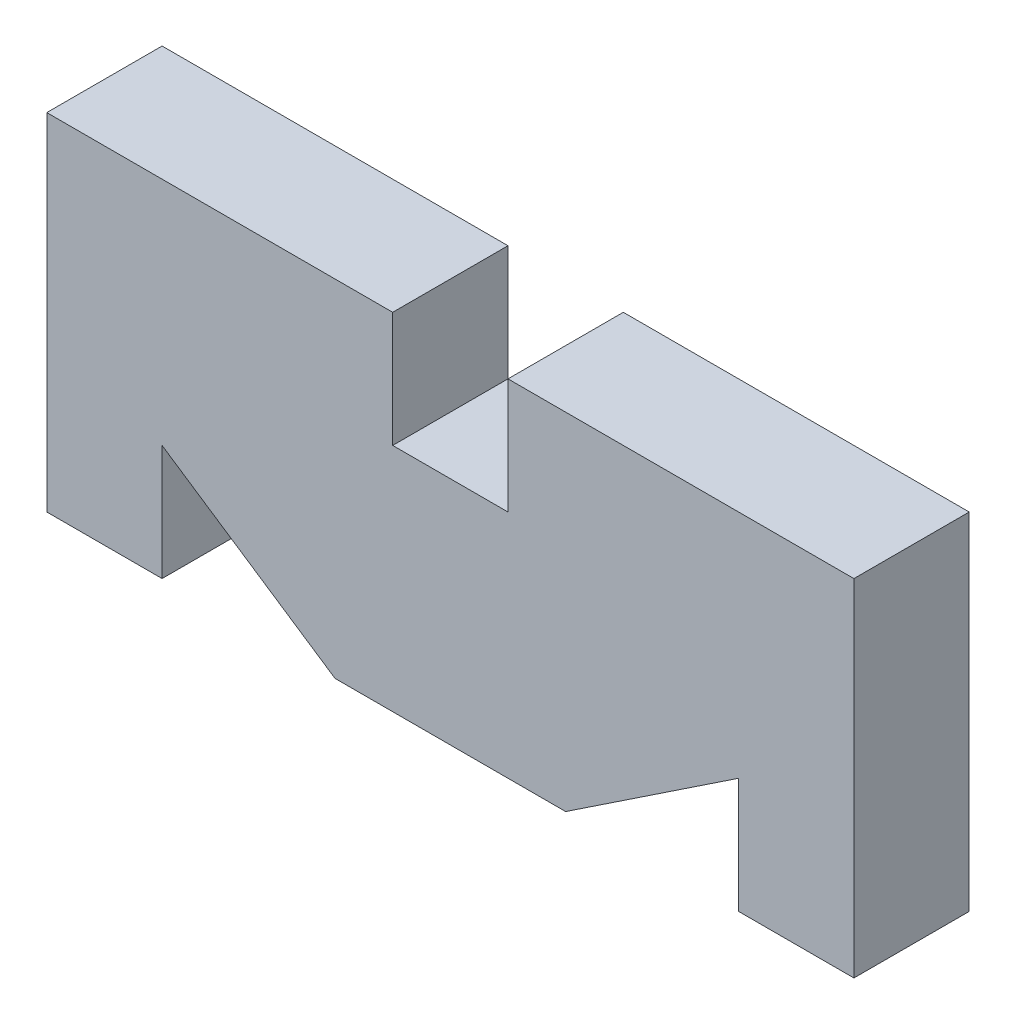
SolidWorks part; units mm, degrees
ref_plane "Front Plane" through (0, 0, 0) normal (0, 0, 1) x (1, 0, 0)
ref_plane "Top Plane" through (0, 0, 0) normal (0, 1, 0) x (1, 0, 0)
ref_plane "Right Plane" through (0, 0, 0) normal (1, 0, 0) x (0, 0, -1)
sketch "Sketch1" plane through (0, 0, 0) normal (0, 0, 1) x (1, 0, 0)
  line L0 (5, 15) -> (35, 15)
  line L1 (-35, 15) -> (-5, 15)
  line L2 (-35, 15) -> (-35, -15)
  line L3 (-35, -15) -> (-25, -15)
  line L4 (35, 15) -> (35, -15)
  line L5 (-35, 15) -> (35, -15) construction
  line L6 (-35, -15) -> (0, 0) construction
  line L8 (-5, 15) -> (-5, 5)
  line L9 (-5, 5) -> (5, 5)
  line L10 (5, 15) -> (5, 5)
  line L11 (-5, 15) -> (5, 5) construction
  line L12 (-5, 5) -> (5, 15) construction
  line L13 (0, 0) -> (0, -15) construction
  line L14 (10, -15) -> (25, -5)
  line L15 (25, -5) -> (25, -15)
  line L16 (25, -15) -> (35, -15)
  line L17 (-25, -5) -> (-25, -15)
  line L18 (-10, -15) -> (-25, -5)
  line L19 (-10, -15) -> (10, -15)
  point P0 (0, 0)
  point P5 (0, 10)
  dimension "D1" = 70
  dimension "D2" = 30
  dimension "D3" = 10
  dimension "D4" = 10
  dimension "D5" = 10
  dimension "D6" = 10
  dimension "D7" = 15
extrude "Boss-Extrude1" add sketch "Sketch1" along normal blind 10
